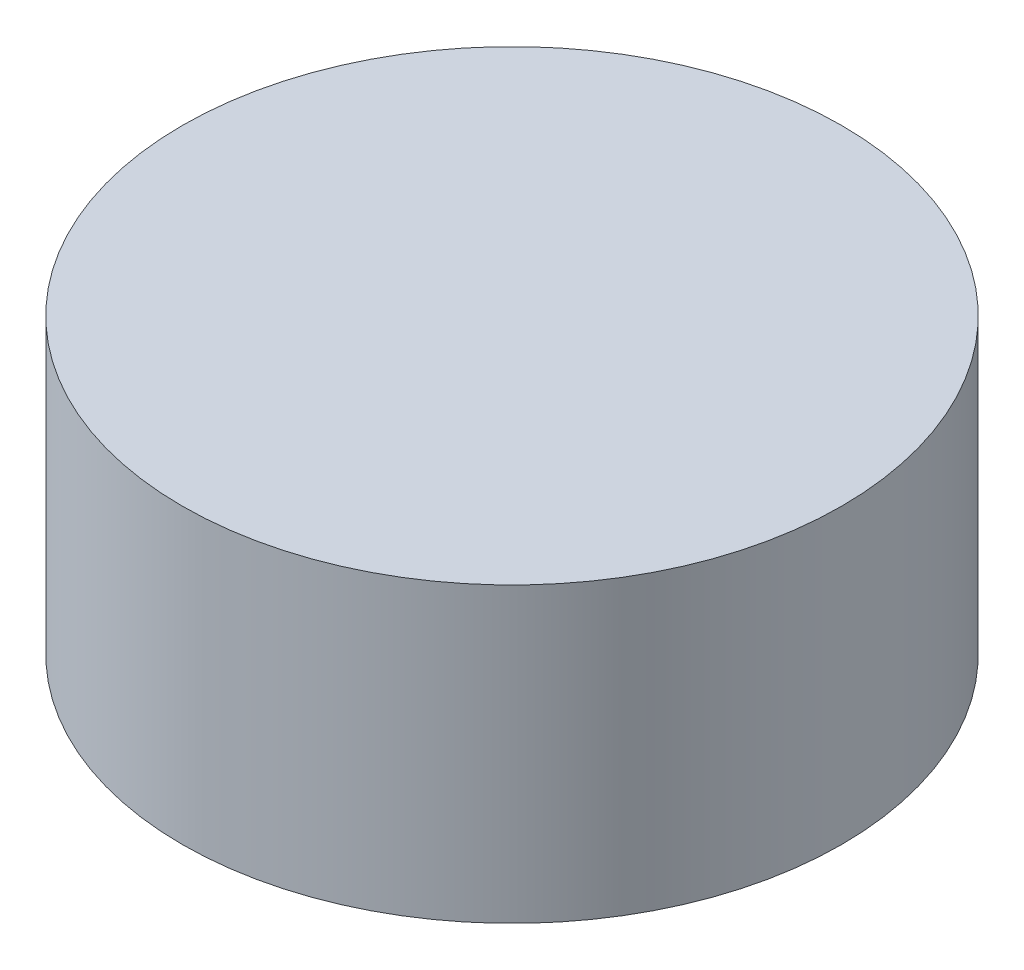
SolidWorks part; units mm, degrees
ref_plane "Front Plane" through (0, 0, 0) normal (0, 0, 1) x (1, 0, 0)
ref_plane "Top Plane" through (0, 0, 0) normal (0, 1, 0) x (1, 0, 0)
ref_plane "Right Plane" through (0, 0, 0) normal (1, 0, 0) x (0, 0, -1)
sketch "Sketch1" plane through (0, 0, 0) normal (0, 1, 0) x (1, 0, 0)
  circle A0 centre (0, 0) radius 57.15
  dimension "D1" = 114.3
extrude "Boss-Extrude1" add sketch "Sketch1" along normal blind 50.8
sketch "Sketch2" plane through (0, 0, 0) normal (0, -1, 0) x (1, 0, 0)
  line L2 (55.75, 3.81) -> (50.6569, 3.81)
  line L3 (55.75, -3.81) -> (50.6569, -3.81)
  line L4 (-55.75, 3.81) -> (-50.6569, 3.81)
  line L5 (-55.75, -3.81) -> (-50.6569, -3.81)
  arc A0 (-50.6569, -3.81) -> (50.6569, -3.81) centre (0, 0) ccw
  arc A1 (55.75, -3.81) -> (55.75, 3.81) centre (0, 0) ccw
  arc A2 (-55.75, 3.81) -> (-55.75, -3.81) centre (0, 0) ccw
  arc A4 (50.6569, 3.81) -> (-50.6569, 3.81) centre (0, 0) ccw
  point P17 (0, 0)
extrude "Cut-Extrude1" cut sketch "Sketch2" against normal blind 8.89
sketch "Sketch3" plane through (0, 8.89, 0) normal (0, -1, 0) x (1, 0, 0)
  line L8 (3.81, -55.75) -> (3.81, -50.6569)
  line L9 (-3.81, -50.6569) -> (-3.81, -55.75)
  line L12 (-3.81, 55.75) -> (-3.81, 50.6569)
  line L13 (3.81, 50.6569) -> (3.81, 55.75)
  arc A6 (-3.81, -50.6569) -> (3.81, -50.6569) centre (0, 0) ccw
  arc A8 (-3.81, -55.75) -> (3.81, -55.75) centre (0, 0) ccw
  arc A14 (3.81, 55.75) -> (-3.81, 55.75) centre (0, 0) ccw
  arc A20 (3.81, 50.6569) -> (-3.81, 50.6569) centre (0, 0) ccw
  point P30 (0, 0)
extrude "Cut-Extrude3" cut sketch "Sketch3" along normal blind 6.985
sketch "Sketch4" plane through (0, 8.89, 0) normal (0, -1, 0) x (1, 0, 0)
  line L1 (-55.75, -3.81) -> (-50.6569, -3.81) construction
  line L7 (3.81, 50.6569) -> (3.81, 55.75) construction
  line L8 (55.75, 3.81) -> (50.6569, 3.81) construction
  line L9 (55.75, 3.81) -> (50.6569, 3.81)
  line L10 (3.81, 50.6569) -> (3.81, 55.75)
  line L11 (-55.75, -3.81) -> (-50.6569, -3.81)
  line L12 (-3.81, -50.6569) -> (-3.81, -55.75) construction
  line L13 (-3.81, -50.6569) -> (-3.81, -55.75)
  arc A0 (-55.75, -3.81) -> (-3.81, -55.75) centre (0, 0) ccw
  arc A1 (-50.6569, -3.81) -> (-3.81, -50.6569) centre (0, 0) ccw
  arc A2 (50.6569, 3.81) -> (3.81, 50.6569) centre (0, 0) ccw
  arc A3 (55.75, 3.81) -> (3.81, 55.75) centre (0, 0) ccw
extrude "Cut-Extrude5" cut sketch "Sketch4" along normal blind 3.81
